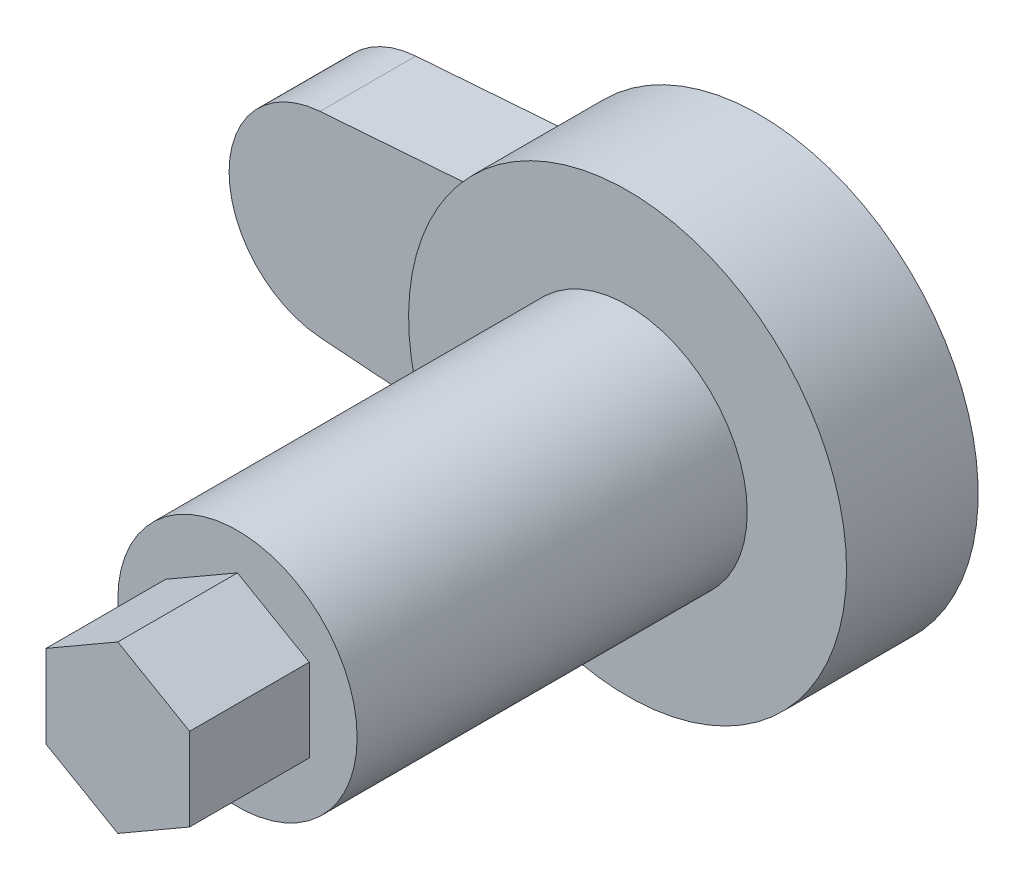
SolidWorks part; units mm, degrees
ref_plane "Front Plane" through (0, 0, 0) normal (0, 0, 1) x (1, 0, 0)
ref_plane "Top Plane" through (0, 0, 0) normal (0, 1, 0) x (1, 0, 0)
ref_plane "Right Plane" through (0, 0, 0) normal (1, 0, 0) x (0, 0, -1)
sketch "servo arm cutout" plane through (0, 0, 0) normal (0, 0, 1) x (1, 0, 0)
  line L5 (0, 0) -> (-14.05, 0) construction
  line L11 (-14.1968, 1.9946) -> (-1.8657, 2.902) construction
  line L12 (-1.8657, -2.902) -> (-14.1968, -1.9946) construction
  line L13 (-14.2041, 2.0943) -> (-1.8982, 2.9999)
  line L14 (-1.8982, -2.9999) -> (-14.2041, -2.0943)
  arc A8 (-1.8657, -2.902) -> (-1.8657, 2.902) centre (0, 0) ccw construction
  arc A9 (-14.1968, 1.9946) -> (-14.1968, -1.9946) centre (-14.05, 0) ccw construction
  arc A10 (-1.8982, -2.9999) -> (-1.8982, 2.9999) centre (0, 0) ccw
  arc A11 (-14.2041, 2.0943) -> (-14.2041, -2.0943) centre (-14.05, 0) ccw
sketch "Sketch6" plane through (0, 0, 0) normal (0, 0, 1) x (1, 0, 0)
  line L10 (-14.3509, -4.0889) -> (-2.4862, -4.962)
  line L11 (-2.4862, 4.962) -> (-14.3509, 4.0889)
  line L12 (-14.3509, -4.0889) -> (-2.4862, -4.962)
  line L13 (-2.4862, 4.962) -> (-14.3509, 4.0889)
  arc A10 (-14.3509, 4.0889) -> (-14.3509, -4.0889) centre (-14.05, 0) ccw
  arc A11 (-2.4862, -4.962) -> (-2.4862, 4.962) centre (0, 0) ccw
  arc A12 (-14.3509, 4.0889) -> (-14.3509, -4.0889) centre (-14.05, 0) ccw
  arc A13 (-2.4862, -4.962) -> (-2.4862, 4.962) centre (0, 0) ccw
  dimension "D1" = 2
extrude "Boss-Extrude2" add sketch "Sketch6" along normal blind 4
sketch "Sketch9" plane through (0, 0, 0) normal (0, 0, 1) x (1, 0, 0)
  circle A0 centre (0, 0) radius 9.15
  arc A1 (-9.1187, 0.7563) -> (2.5, 8.8018) centre (0, 0) ccw construction
extrude "Boss-Extrude5" add sketch "Sketch9" along normal blind 5.5
sketch "Sketch11" plane through (0, 0, 0) normal (0, 0, -1) x (-1, 0, 0)
  line L2 (14.2041, 2.0943) -> (1.8982, 2.9999)
  line L3 (1.8982, -2.9999) -> (14.2041, -2.0943)
  line L4 (14.2041, 2.0943) -> (1.8982, 2.9999)
  line L5 (1.8982, -2.9999) -> (14.2041, -2.0943)
  arc A2 (1.8982, 2.9999) -> (1.8982, -2.9999) centre (0, 0) ccw
  arc A3 (14.2041, -2.0943) -> (14.2041, 2.0943) centre (14.05, 0) ccw
  arc A4 (1.8982, 2.9999) -> (1.8982, -2.9999) centre (0, 0) ccw
  arc A5 (14.2041, -2.0943) -> (14.2041, 2.0943) centre (14.05, 0) ccw
  dimension "D1" = 0
extrude "Cut-Extrude1" cut sketch "Sketch11" against normal blind 3
sketch "Sketch7" plane through (0, 0, 5.5) normal (0, 0, 1) x (1, 0, 0)
  circle A0 centre (0, 0) radius 5
  dimension "D1" = 10
extrude "Boss-Extrude3" add sketch "Sketch7" along normal blind 16.3
sketch "Sketch8" plane through (0, 0, 21.8) normal (0, 0, 1) x (1, 0, 0)
  line L1 (0, 3.4641) -> (-3, 1.7321)
  line L2 (-3, 1.7321) -> (-3, -1.7321)
  line L3 (-3, -1.7321) -> (0, -3.4641)
  line L4 (0, -3.4641) -> (3, -1.7321)
  line L5 (3, -1.7321) -> (3, 1.7321)
  line L6 (3, 1.7321) -> (0, 3.4641)
  circle A0 centre (0, 0) radius 3 construction
  dimension "D1" = 6
extrude "Boss-Extrude4" add sketch "Sketch8" along normal blind 5
